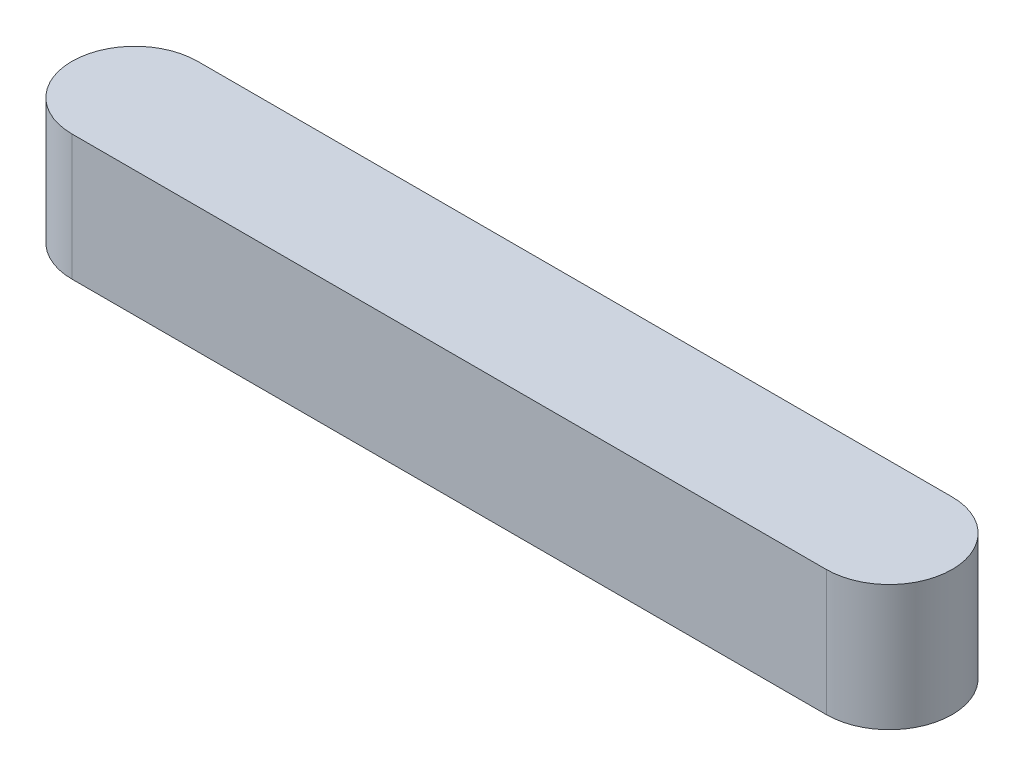
SolidWorks part; units mm, degrees
ref_plane "Front Plane" through (0, 0, 0) normal (0, 0, 1) x (1, 0, 0)
ref_plane "Top Plane" through (0, 0, 0) normal (0, 1, 0) x (1, 0, 0)
ref_plane "Right Plane" through (0, 0, 0) normal (1, 0, 0) x (0, 0, -1)
sketch "Sketch3" plane through (0, 0, 0) normal (0, 1, 0) x (1, 0, 0)
  line L0 (-60, 0) -> (60, 0) construction
  line L1 (-60, 10) -> (60, 10)
  line L2 (-60, -10) -> (60, -10)
  arc A0 (-60, 10) -> (-60, -10) centre (-60, 0) ccw
  arc A1 (60, -10) -> (60, 10) centre (60, 0) ccw
  point P3 (0, 0)
  point P10 (20, 0)
  dimension "D1" = 10
  dimension "D2" = 120
  dimension "D3" = 40
extrude "Boss-Extrude1" add sketch "Sketch3" along normal blind 20 contours L1 A1 L2 A0
equation "\"TibiaRadius\"= 10mm"
equation "\"TibiaThickness\"= 20mm"
equation "\"D1@Sketch3\"= \"TibiaRadius\""
equation "\"D1@Boss-Extrude1\"= \"TibiaThickness\""
equation "\"D3@Sketch3\"= \"D2@Sketch3\" / 3"
equation "\"FibulaLength\" = 120mm"
equation "\"D2@Sketch3\"= \"FibulaLength\""
